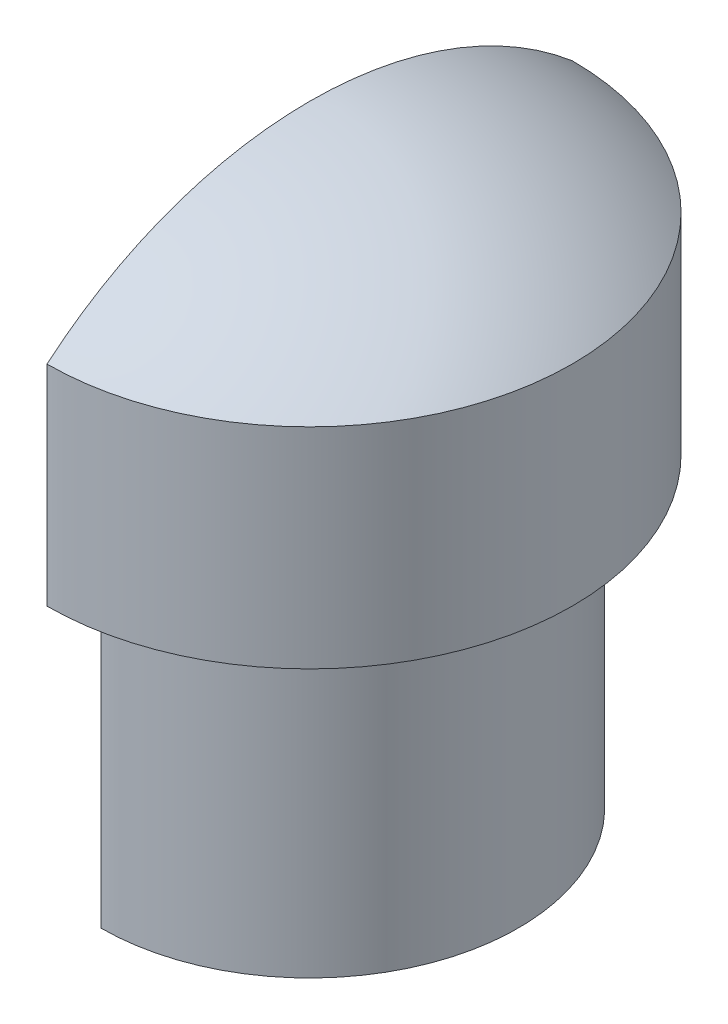
SolidWorks part; units mm, degrees
ref_plane "Front Plane" through (0, 0, 0) normal (0, 0, 1) x (1, 0, 0)
ref_plane "Top Plane" through (0, 0, 0) normal (0, 1, 0) x (1, 0, 0)
ref_plane "Right Plane" through (0, 0, 0) normal (1, 0, 0) x (0, 0, -1)
sketch "Sketch1" plane through (0, 0, 0) normal (0, 1, 0) x (1, 0, 0)
  circle A0 centre (0, 0) radius 2.9
  dimension "D1" = 5.8
extrude "Boss-Extrude1" add sketch "Sketch1" along normal blind 5
sketch "Sketch2" plane through (0, 5, 0) normal (0, 1, 0) x (1, 0, 0)
  circle A1 centre (0, 0) radius 1.4
  circle A2 centre (0, 0) radius 2.9
  circle A4 centre (0, 0) radius 2.9 construction
  dimension "D1" = 0
  dimension "D2" = 1.5
extrude "Cut-Extrude1" cut sketch "Sketch2" against normal up to next
sketch "Sketch6" plane through (0, 0, 0) normal (0, 0, 1) x (1, 0, 0)
  line L1 (0, 5) -> (1.4, 5) construction
  line L2 (1.4, 5) -> (-1.4, 5) construction
  line L3 (0, 5) -> (0, 8.5) construction
  line L4 (0, -2.75) -> (0, 2.75) construction
  line L5 (2.9, 6.8) -> (2.9, 5)
  line L6 (3.65, 7.1632) -> (3.65, 5)
  line L7 (0, 8.5) -> (-2.9, 8.5) construction
  line L8 (-2.9, 8.5) -> (-2.9, 5) construction
  line L11 (3.65, 4.25) -> (3.65, 5)
  line L12 (0, 7.75) -> (0, 8.5)
  line L13 (2.9, 6.8) -> (2.9, 5) construction
  line L14 (3.65, 4.25) -> (2.9, 4.25)
  line L15 (2.9, 4.25) -> (2.9, 5)
  line L16 (2.9, 5) -> (3.65, 5) construction
  arc A0 (0, 8.5) -> (3.65, 7.1632) centre (0, 2.8487) cw
  arc A1 (0, 7.75) -> (2.9, 6.8) centre (0, 2.8487) cw
  point P2 (0, 0)
  point P20 (0, 0)
  dimension "D1" = 0.75
  dimension "D2" = 1.8
  dimension "D3" = 0.75
  dimension "D4" = 3.5
revolve "Revolve2" add sketch "Sketch6" angle 360 about L3
sketch "Sketch8" plane through (0, 0, 0) normal (0, 1, 0) x (1, 0, 0)
  line L0 (0, -2.75) -> (0, 2.75) construction
  line L1 (0, 3.65) -> (-3.65, 3.65)
  line L2 (0, 3.65) -> (0, -3.65)
  line L3 (0, -3.65) -> (-3.65, -3.65)
  line L4 (-3.65, 3.65) -> (-3.65, -3.65)
  circle A0 centre (0, 0) radius 3.65 construction
extrude "Cut-Extrude2" cut sketch "Sketch8" along normal up to next
